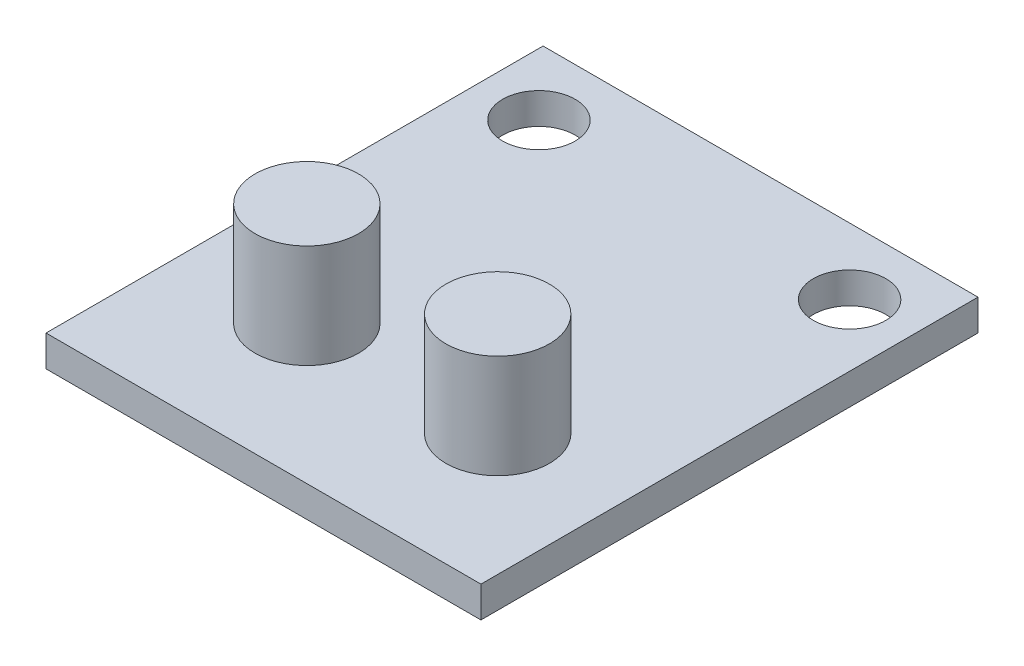
SolidWorks part; units mm, degrees
ref_plane "前视基准面" through (0, 0, 0) normal (0, 0, 1) x (1, 0, 0)
ref_plane "上视基准面" through (0, 0, 0) normal (0, 1, 0) x (1, 0, 0)
ref_plane "右视基准面" through (0, 0, 0) normal (1, 0, 0) x (0, 0, -1)
sketch "草图1" plane through (0, 0, 0) normal (0, 1, 0) x (1, 0, 0)
  line L1 (-10.5, 12) -> (10.5, 12)
  line L2 (-10.5, 12) -> (-10.5, -12)
  line L3 (-10.5, -12) -> (10.5, -12)
  line L4 (10.5, 12) -> (10.5, -12)
  line L5 (-10.5, 12) -> (10.5, -12) construction
  line L6 (-10.5, -12) -> (10.5, 12) construction
  point P0 (0, 0)
  dimension "D1" = 24
  dimension "D2" = 21
extrude "凸台-拉伸1" add sketch "草图1" along normal blind 1.5
sketch "草图2" plane through (0, 1.5, 0) normal (0, 1, 0) x (1, 0, 0)
  line L0 (0, 14.0995) -> (0, -15.3435) construction
  line L1 (10.5, -12) -> (10.5, 12) construction
  circle A0 centre (-7.5, 8.8006) radius 1.75
  circle A1 centre (7.5, 8.8006) radius 1.75
  dimension "D1" = 3
extrude "切除-拉伸1" cut sketch "草图2" against normal blind 1.5
sketch "草图3" plane through (0, 1.5, 0) normal (0, 1, 0) x (1, 0, 0)
  line L0 (0, 14.015) -> (0, -14.015) construction
  circle A0 centre (-4.6077, -5.2988) radius 2.5
  circle A1 centre (4.6077, -5.2988) radius 2.5
extrude "凸台-拉伸2" add sketch "草图3" along normal blind 5 contours A0 | A1
